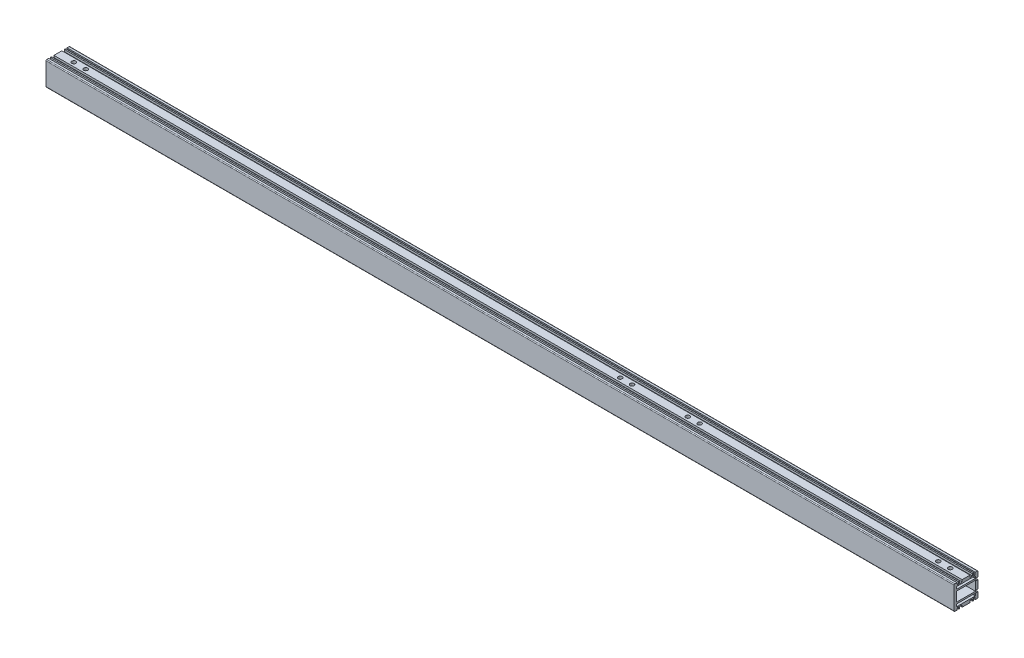
SolidWorks part; units mm, degrees
ref_plane "前视基准面" through (0, 0, 0) normal (0, 0, 1) x (1, 0, 0)
ref_plane "上视基准面" through (0, 0, 0) normal (0, 1, 0) x (1, 0, 0)
ref_plane "右视基准面" through (0, 0, 0) normal (1, 0, 0) x (0, 0, -1)
sketch "草图1" plane through (0, 0, 0) normal (1, 0, 0) x (0, 0, -1)
  line L0 (-15, 15) -> (15, -15) construction
  line L1 (-14, 15) -> (-11.5, 15)
  line L2 (-15, 14) -> (-15, -14)
  line L3 (-14, -15) -> (-11.5, -15)
  line L4 (15, 14) -> (15, 8)
  line L5 (15, 15) -> (-15, -15) construction
  line L6 (-11.5, 15) -> (-11.5, 13.5)
  line L7 (-11.5, 13.5) -> (-11.4, 13.5)
  line L8 (-11, 13.1) -> (-11, 12)
  line L9 (-11, 12) -> (-9.5, 12)
  line L10 (-9.5, 12) -> (-9.5, 15)
  line L11 (-9.5, 15) -> (-8, 15)
  line L12 (-8, 15) -> (-8, 12.5)
  line L13 (-8, 12.5) -> (-5, 12.5)
  line L14 (-5, 12.5) -> (-5, 15)
  line L15 (-5, 15) -> (5, 15)
  line L16 (0, 21.5201) -> (0, -18.309) construction
  line L17 (0, 55) -> (0, -55) construction
  line L18 (5, 12.5) -> (5, 15)
  line L19 (8, 12.5) -> (5, 12.5)
  line L20 (8, 15) -> (8, 12.5)
  line L21 (9.5, 15) -> (8, 15)
  line L22 (9.5, 12) -> (9.5, 15)
  line L23 (11, 12) -> (9.5, 12)
  line L24 (11, 13.1) -> (11, 12)
  line L25 (11.5, 13.5) -> (11.4, 13.5)
  line L26 (11.5, 15) -> (11.5, 13.5)
  line L27 (8, 15) -> (9.5, 15)
  line L28 (11.5, 15) -> (14, 15)
  line L29 (-19.8303, 0) -> (22.13, 0) construction
  line L30 (55, 0) -> (-55, 0) construction
  line L31 (8, -15) -> (9.5, -15)
  line L32 (11.5, -15) -> (11.5, -13.5)
  line L33 (11.5, -13.5) -> (11.4, -13.5)
  line L34 (11, -13.1) -> (11, -12)
  line L35 (11, -12) -> (9.5, -12)
  line L36 (9.5, -12) -> (9.5, -15)
  line L37 (9.5, -15) -> (8, -15)
  line L38 (8, -15) -> (8, -12.5)
  line L39 (8, -12.5) -> (5, -12.5)
  line L40 (5, -12.5) -> (5, -15)
  line L41 (-5, -15) -> (5, -15)
  line L42 (-5, -12.5) -> (-5, -15)
  line L43 (-8, -12.5) -> (-5, -12.5)
  line L44 (-8, -15) -> (-8, -12.5)
  line L45 (-9.5, -15) -> (-8, -15)
  line L46 (-9.5, -12) -> (-9.5, -15)
  line L47 (-11, -12) -> (-9.5, -12)
  line L48 (-11, -13.1) -> (-11, -12)
  line L49 (-11.5, -13.5) -> (-11.4, -13.5)
  line L50 (-11.5, -15) -> (-11.5, -13.5)
  line L51 (-9.5, -15) -> (-8, -15)
  line L52 (-5, -15) -> (5, -15)
  line L53 (8, -15) -> (9.5, -15)
  line L54 (11.5, -15) -> (14, -15)
  line L55 (15, 8) -> (12.5, 8)
  line L56 (12.5, 8) -> (12.5, 5)
  line L57 (12.5, 5) -> (15, 5)
  line L58 (12.5, -5) -> (15, -5)
  line L59 (12.5, -8) -> (12.5, -5)
  line L60 (15, -8) -> (12.5, -8)
  line L61 (15, 5) -> (15, -5)
  line L62 (15, -8) -> (15, -14)
  line L63 (12, -10.5) -> (12, -8.5)
  line L64 (-11.5, 11) -> (11.5, 11)
  line L65 (-12, 10.5) -> (-12, 8.5)
  line L66 (-11.5, 8) -> (11.5, 8)
  line L67 (12, 10.5) -> (12, 8.5)
  line L68 (-11.5, -8) -> (11.5, -8)
  line L69 (-12, -10.5) -> (-12, -8.5)
  line L70 (-11.5, -11) -> (11.5, -11)
  line L72 (-11.75, 6) -> (11.75, 6)
  line L73 (-11.75, 6) -> (-11.75, -6)
  line L74 (-11.75, -6) -> (11.75, -6)
  line L75 (11.75, 6) -> (11.75, -6)
  arc A0 (12, 8.5) -> (11.5, 8) centre (11.5, 8.5) cw
  arc A1 (11.5, 11) -> (12, 10.5) centre (11.5, 10.5) cw
  arc A2 (-11.5, 11) -> (-12, 10.5) centre (-11.5, 10.5) ccw
  arc A3 (-11.5, 8) -> (-12, 8.5) centre (-11.5, 8.5) cw
  arc A4 (-11, -13.1) -> (-11.4, -13.5) centre (-11.4, -13.1) cw
  arc A5 (11.4, -13.5) -> (11, -13.1) centre (11.4, -13.1) cw
  arc A6 (11.4, 13.5) -> (11, 13.1) centre (11.4, 13.1) ccw
  arc A7 (-11, 13.1) -> (-11.4, 13.5) centre (-11.4, 13.1) ccw
  arc A8 (-11.5, -8) -> (-12, -8.5) centre (-11.5, -8.5) ccw
  arc A9 (-11.5, -11) -> (-12, -10.5) centre (-11.5, -10.5) cw
  arc A10 (11.5, -11) -> (12, -10.5) centre (11.5, -10.5) ccw
  arc A11 (12, -8.5) -> (11.5, -8) centre (11.5, -8.5) ccw
  arc A12 (14, 15) -> (15, 14) centre (14, 14) cw
  arc A13 (14, -15) -> (15, -14) centre (14, -14) ccw
  arc A14 (-15, -14) -> (-14, -15) centre (-14, -14) ccw
  arc A15 (-15, 14) -> (-14, 15) centre (-14, 14) cw
  point P69 (12, 11)
  point P72 (-12, 11)
  point P77 (-11, -13.5)
  point P80 (11, -13.5)
  point P83 (11, 13.5)
  point P86 (-11, 13.5)
  point P99 (-12, -11)
  point P100 (12, -11)
  dimension "D17" = 0.5
  dimension "D18" = 0.4
  dimension "D21" = 1
  dimension "D1" = 3.5
  dimension "D2" = 1.5
  dimension "D3" = 0.5
  dimension "D4" = 1.5
  dimension "D5" = 3
  dimension "D6" = 30
  dimension "D7" = 30
  dimension "D8" = 1.5
  dimension "D9" = 2.5
  dimension "D10" = 3
  dimension "D11" = 2.5
  dimension "D12" = 7
  dimension "D13" = 3
  dimension "D14" = 4
  dimension "D15" = 3
  dimension "D16" = 24
  dimension "D19" = 23.5
  dimension "D20" = 12
extrude "凸台-拉伸1" add sketch "草图1" along normal mid plane 1142 contours A15 L2 A14 L3 L50 L49 A4 L48 L47 L46 L45 L44 L43 L42 L41 L40 L39 L38 L31 L36 L35 L34 A5 L33 L32 L54 A13 L62 L60 L59 L58 L61 L57 L56 L55 L4 A12 L28 L26 L25 A6 L24 L23 L22 L21 L20 L19 L18 L15 L14 L13
hole_wizard "M6 螺纹孔1" positions "草图4" profile "草图3" tap size "M6" standard "GB"
sketch "草图4" plane through (0, -15, 0) normal (0, -1, 0) x (1, 0, 0)
  line L0 (571, 5) -> (571, -5) construction
  line L1 (571, 15) -> (-571, 15) construction
  point P0 (551, 0)
  point P1 (536, 0)
  point P4 (-536, 0)
  point P7 (-551, 0)
  dimension "D1" = 20
  dimension "D2" = 15
sketch "草图3" plane through (551, -15, 0) normal (1, 0, 0) x (0, 0, -1)
  line L0 (0, 0) -> (0, 16.5022)
  line L1 (0, 16.5022) -> (2.5, 15)
  line L2 (2.5, 15) -> (2.5, 0)
  line L5 (2.5, 0) -> (0, 0)
  line L10 (0, 16.5022) -> (-2.5, 15) construction
  line L11 (0, -6.35) -> (0, 107.95) construction
  dimension "螺纹孔钻头直径" = 5
  dimension "螺纹孔钻头深度" = 15
  dimension "导头角度" = 118
cosmetic thread "孔螺蚊线1" parameters "D1"=9, "D2"=6
cosmetic thread "孔螺蚊线2" parameters "D1"=9, "D2"=6
cosmetic thread "孔螺蚊线3" parameters "D1"=9, "D2"=6
cosmetic thread "孔螺蚊线4" parameters "D1"=9, "D2"=6
hole_wizard "M6 螺纹孔2" positions "草图6" profile "草图5" tap size "M6" standard "GB"
sketch "草图6" plane through (0, 15, 0) normal (0, 1, 0) x (-1, 0, 0)
  line L0 (571, 5) -> (571, -5) construction
  line L1 (-571, 15) -> (571, 15) construction
  point P0 (551, 0)
  point P1 (536, 0)
  point P4 (-151, 0)
  point P7 (-136, 0)
  point P10 (-221, 0)
  point P13 (-236, 0)
  point P16 (-536, 0)
  point P19 (-551, 0)
  dimension "D1" = 20
  dimension "D2" = 15
sketch "草图5" plane through (-551, 15, 0) normal (1, 0, 0) x (0, 0, 1)
  line L0 (0, 0) -> (0, 16.5022)
  line L1 (0, 16.5022) -> (2.5, 15)
  line L2 (2.5, 15) -> (2.5, 0)
  line L5 (2.5, 0) -> (0, 0)
  line L10 (0, 16.5022) -> (-2.5, 15) construction
  line L11 (0, -6.35) -> (0, 107.95) construction
  dimension "螺纹孔钻头直径" = 5
  dimension "螺纹孔钻头深度" = 15
  dimension "导头角度" = 118
cosmetic thread "孔螺蚊线5" parameters "D1"=9, "D2"=6
cosmetic thread "孔螺蚊线6" parameters "D1"=9, "D2"=6
cosmetic thread "孔螺蚊线7" parameters "D1"=9, "D2"=6
cosmetic thread "孔螺蚊线8" parameters "D1"=9, "D2"=6
cosmetic thread "孔螺蚊线9" parameters "D1"=9, "D2"=6
cosmetic thread "孔螺蚊线10" parameters "D1"=9, "D2"=6
cosmetic thread "孔螺蚊线11" parameters "D1"=9, "D2"=6
cosmetic thread "孔螺蚊线12" parameters "D1"=9, "D2"=6
hole_wizard "M4 螺纹孔1" positions "草图8" profile "草图7" tap size "M4" standard "GB"
sketch "草图8" plane through (0, -15, 0) normal (0, -1, 0) x (1, 0, 0)
  line L0 (571, 14) -> (571, 11.5) construction
  line L1 (571, 15) -> (-571, 15) construction
  point P1 (479, 0)
  point P3 (319, 0)
  point P5 (159, 0)
  point P7 (-1, 0)
  point P9 (-161, 0)
  point P11 (-321, 0)
  point P13 (-481, 0)
  dimension "D1" = 92
  dimension "D2" = 15
  dimension "D3" = 160
  dimension "D4" = 15
  dimension "D5" = 160
  dimension "D6" = 15
  dimension "D7" = 160
  dimension "D8" = 15
  dimension "D9" = 160
  dimension "D10" = 15
  dimension "D11" = 160
  dimension "D12" = 15
  dimension "D13" = 160
  dimension "D14" = 15
sketch "草图7" plane through (479, -15, 0) normal (1, 0, 0) x (0, 0, -1)
  line L0 (0, 0) -> (0, 11.0914)
  line L1 (0, 11.0914) -> (1.65, 10.1)
  line L2 (1.65, 10.1) -> (1.65, 0)
  line L5 (1.65, 0) -> (0, 0)
  line L10 (0, 11.0914) -> (-1.65, 10.1) construction
  line L11 (0, -6.35) -> (0, 107.95) construction
  dimension "螺纹孔钻头直径" = 3.3
  dimension "螺纹孔钻头深度" = 10.1
  dimension "导头角度" = 118
cosmetic thread "孔螺蚊线13" parameters "D1"=8, "D2"=4
cosmetic thread "孔螺蚊线14" parameters "D1"=8, "D2"=4
cosmetic thread "孔螺蚊线15" parameters "D1"=8, "D2"=4
cosmetic thread "孔螺蚊线16" parameters "D1"=8, "D2"=4
cosmetic thread "孔螺蚊线17" parameters "D1"=8, "D2"=4
cosmetic thread "孔螺蚊线18" parameters "D1"=8, "D2"=4
cosmetic thread "孔螺蚊线19" parameters "D1"=8, "D2"=4
hole_wizard "M6 螺纹孔3" positions "草图10" profile "草图9" tap size "M6" standard "GB"
sketch "草图10" plane through (0, 0, -15) normal (0, 0, -1) x (-1, 0, 0)
  line L0 (-571, -15) -> (571, -15) construction
  line L1 (-571, 5) -> (-571, -5) construction
  point P0 (-293.5, 0)
  point P1 (-218.5, 0)
  dimension "D1" = 15
  dimension "D2" = 15
  dimension "D3" = 75
  dimension "D4" = 277.5
sketch "草图9" plane through (293.5, 0, -15) normal (1, 0, 0) x (0, 1, 0)
  line L0 (0, 0) -> (0, 16.5022)
  line L1 (0, 16.5022) -> (2.5, 15)
  line L2 (2.5, 15) -> (2.5, 0)
  line L5 (2.5, 0) -> (0, 0)
  line L10 (0, 16.5022) -> (-2.5, 15) construction
  line L11 (0, -6.35) -> (0, 107.95) construction
  dimension "螺纹孔钻头直径" = 5
  dimension "螺纹孔钻头深度" = 15
  dimension "导头角度" = 118
cosmetic thread "孔螺蚊线20" parameters "D1"=3.25, "D2"=6
cosmetic thread "孔螺蚊线21" parameters "D1"=3.25, "D2"=6
